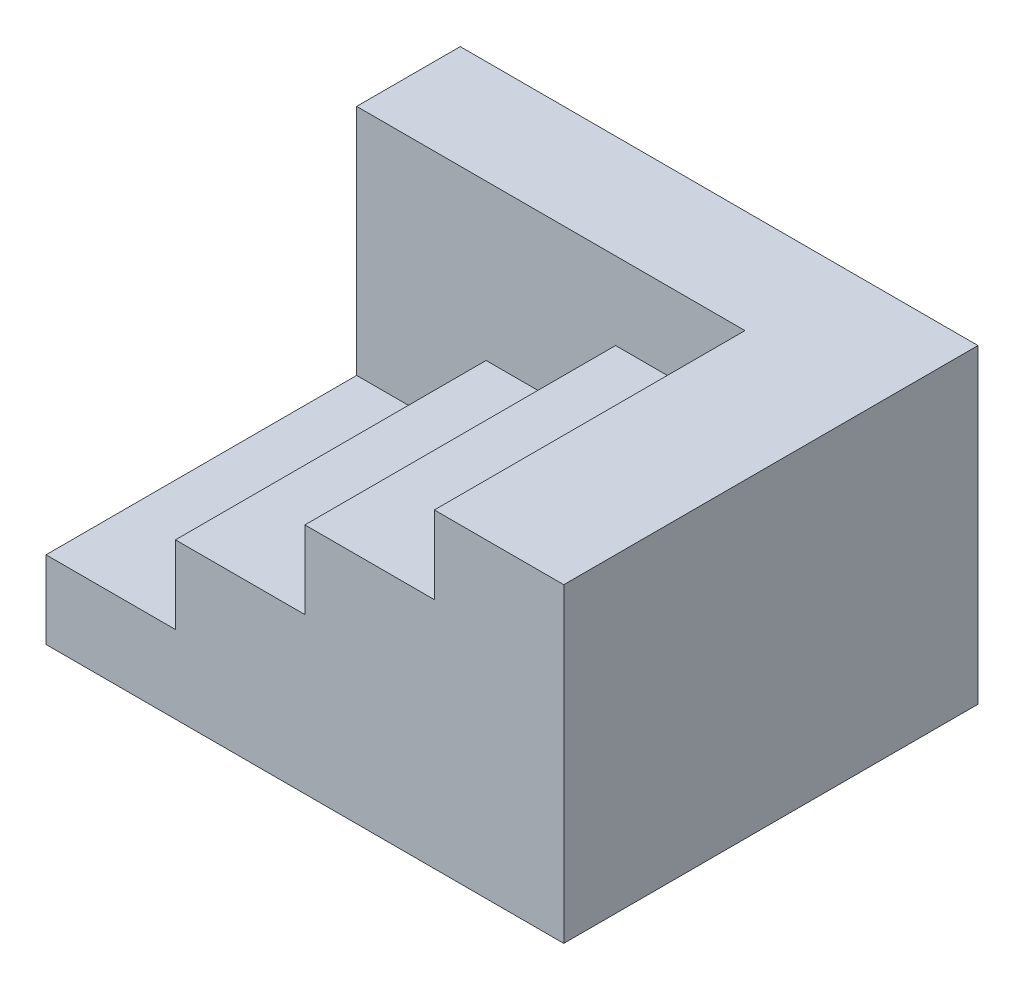
SolidWorks part; units mm, degrees
ref_plane "Front Plane" through (0, 0, 0) normal (0, 0, 1) x (1, 0, 0)
ref_plane "Top Plane" through (0, 0, 0) normal (0, 1, 0) x (1, 0, 0)
ref_plane "Right Plane" through (0, 0, 0) normal (1, 0, 0) x (0, 0, -1)
sketch "Sketch1" plane through (0, 0, 0) normal (0, 1, 0) x (1, 0, 0)
  line L1 (-64.7044, 45.1458) -> (35.2956, 45.1458)
  line L2 (-64.7044, 45.1458) -> (-64.7044, -34.8542)
  line L3 (-64.7044, -34.8542) -> (35.2956, -34.8542)
  line L4 (35.2956, 45.1458) -> (35.2956, -34.8542)
  point P4 (0, 0)
  dimension "D1" = 80
  dimension "D2" = 100
extrude "Boss-Extrude1" add sketch "Sketch1" against normal blind 60
sketch "Sketch3" plane through (0, 0, 34.8542) normal (0, 0, 1) x (1, 0, 0)
  line L0 (-64.7044, 0) -> (10.2956, 0)
  line L1 (-64.7044, 0) -> (35.2956, 0) construction
  line L2 (10.2956, 0) -> (10.2956, -15)
  line L3 (10.2956, -15) -> (-14.7044, -15)
  line L4 (-14.7044, -15) -> (-14.7044, -30)
  line L5 (-14.7044, -30) -> (-39.7044, -30)
  line L6 (-39.7044, -30) -> (-39.7044, -45)
  line L7 (-39.7044, -45) -> (-64.7044, -45)
  line L8 (-64.7044, -60) -> (-64.7044, 0) construction
  line L9 (-64.7044, -45) -> (-64.7044, 0)
  point P5 (0, 0)
  dimension "D1" = 15
  dimension "D2" = 25
extrude "Cut-Extrude1" cut sketch "Sketch3" against normal blind 60
